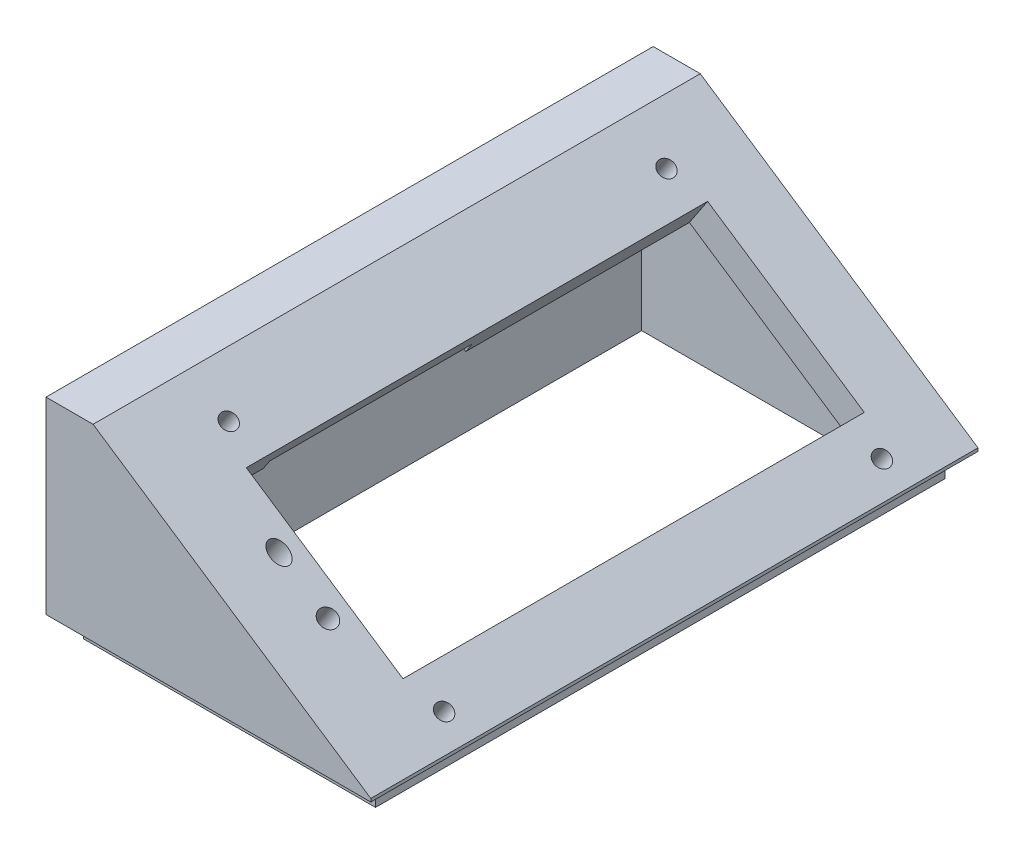
SolidWorks part; units mm, degrees
ref_plane "Front Plane" through (0, 0, 0) normal (0, 0, 1) x (1, 0, 0)
ref_plane "Top Plane" through (0, 0, 0) normal (0, 1, 0) x (1, 0, 0)
ref_plane "Right Plane" through (0, 0, 0) normal (1, 0, 0) x (0, 0, -1)
sketch "Sketch1" plane through (0, 0, 0) normal (0, 0, 1) x (1, 0, 0)
  line L0 (0, 0) -> (70, 0)
  line L1 (0, 0) -> (0, 40)
  line L3 (0, 40) -> (10, 40)
  line L4 (10, 40) -> (70, 0)
  dimension "D1" = 40
  dimension "D2" = 70
  dimension "D3" = 10
extrude "Boss-Extrude1" add sketch "Sketch1" along normal mid plane 129
sketch "Sketch3" plane through (0, 0, 0) normal (0, -1, 0) x (1, 0, 0)
  line L0 (0, 0) -> (4, 0) construction
  line L1 (4, 60.5) -> (66, 60.5)
  line L2 (4, 60.5) -> (4, -60.5)
  line L3 (4, -60.5) -> (66, -60.5)
  line L4 (66, 60.5) -> (66, -60.5)
  line L5 (0, 64.5) -> (0, -64.5) construction
  line L6 (35, 64.5) -> (35, 60.5) construction
  line L7 (0, 64.5) -> (70, 64.5) construction
  line L8 (70, 64.5) -> (70, -64.5) construction
  dimension "D1" = 4
  dimension "D2" = 4
extrude "Boss-Extrude3" add sketch "Sketch3" along normal blind 4.5
ref_plane "Plane1" through (0, 0, 55.5) normal (0, 0, 1) x (1, 0, 0)
sketch "Sketch6" plane through (21.5385, 32.3077, 0) normal (0.5547, 0.8321, 0) x (0.8321, -0.5547, 0)
  line L0 (58.2435, -64.5) -> (-13.8675, -64.5) construction
  line L1 (3.6325, -46.5) -> (43.6325, -46.5)
  line L2 (3.6325, -46.5) -> (3.6325, 51.5)
  line L3 (3.6325, 51.5) -> (43.6325, 51.5)
  line L4 (43.6325, -46.5) -> (43.6325, 51.5)
  line L5 (4.1325, 51) -> (4.1325, -46) construction
  dimension "D1" = 98
  dimension "D2" = 18
  dimension "D3" = 40
  dimension "D4" = 0.5
extrude "Cut-Extrude3" cut sketch "Sketch6" against normal blind 7
sketch "Sketch5" plane through (0, -4.5, 0) normal (0, -1, 0) x (1, 0, 0)
  line L0 (66, 60.5) -> (4, 60.5) construction
  line L1 (6.56, 55.5) -> (63.8, 55.5)
  line L2 (6.56, 55.5) -> (6.56, -55.5)
  line L3 (6.56, -55.5) -> (63.8, -55.5)
  line L4 (63.8, 55.5) -> (63.8, -55.5)
  line L6 (4, 60.5) -> (4, -60.5) construction
  line L8 (4, -60.5) -> (66, -60.5) construction
  line L9 (66, -60.5) -> (66, 60.5) construction
  dimension "D1" = 5
  dimension "D2" = 2.2
  dimension "D3" = 5
  dimension "D4" = 2.56
extrude "Cut-Extrude2" cut sketch "Sketch5" against normal blind 1.23
sketch "Sketch4" plane through (0, 0, 55.5) normal (0, 0, 1) x (1, 0, 0)
  line L3 (63.7805, -4.2666) -> (6.5585, 33.8813)
  line L4 (6.5585, 33.8813) -> (6.5585, -4.5)
  line L6 (53.96, 2.2804) -> (20.678, 24.4684) construction
  line L7 (63.7805, -4.2666) -> (63.7805, -4.5)
  line L8 (63.7805, -4.5) -> (6.5585, -4.5)
  line L9 (95, -4.5) -> (-76.75, -4.5) construction
  dimension "D1" = 1.5
  dimension "D2" = 1.5
extrude "Cut-Extrude1" cut sketch "Sketch4" against normal up to surface (111 mm away) up to face at (35.18, -3.885, -55.5)
sketch "Sketch7" plane through (21.5385, 32.3077, 0) normal (0.5547, 0.8321, 0) x (0.8321, -0.5547, 0)
  line L0 (3.6325, -46.5) -> (43.6325, -46.5) construction
  line L1 (17.3825, -51) -> (29.8825, -51) construction
  line L2 (23.6325, -51) -> (23.6325, -46.5) construction
  line L3 (14.8825, -51) -> (17.3825, -51) construction
  circle A0 centre (29.8825, -51) radius 1.925
  ellipse E0 centre (17.3825, -51) end of major axis (19.8825, -51) minor radius 1.85
  dimension "D1" = 3.85
  dimension "D2" = 12.5
  dimension "D3" = 4.5
extrude "Cut-Extrude4" cut sketch "Sketch7" against normal up to next
hole_wizard "Ø1.0mm Dowel Hole1" positions "Sketch8" profile "Sketch9" hole size "Ø1.0" standard "ANSI Metric"
sketch "Sketch8" plane through (21.5385, 32.3077, 0) normal (0.5547, 0.8321, 0) x (0.8321, -0.5547, 0)
  point P0 (-3.8675, -44)
  point P2 (-3.8675, 49)
  point P4 (51.1325, 49)
  point P6 (51.1325, -44)
sketch "Sketch9" plane through (18.3205, 34.453, 44) normal (0, 0, 1) x (-0.8321, 0.5547, 0)
  line L0 (0, 0) -> (0, 7)
  line L1 (0, 7) -> (1.75, 7)
  line L2 (1.75, 7) -> (1.75, 0)
  line L5 (1.75, 0) -> (0, 0)
  line L11 (0, -6.35) -> (0, 107.95) construction
  dimension "Thru Hole Dia." = 3.5
  dimension "Thru Hole Depth" = 7
sketch "Sketch10" plane through (0, 0, 0) normal (-1, 0, 0) x (0, 0, 1)
  line L0 (64.5, 40) -> (64.5, 0) construction
  line L1 (35.5, 3) -> (55.5, 3)
  line L2 (35.5, 3) -> (35.5, 16)
  line L3 (35.5, 16) -> (55.5, 16)
  line L4 (55.5, 3) -> (55.5, 16)
  line L5 (64.5, 0) -> (-64.5, 0) construction
  dimension "D1" = 20
  dimension "D2" = 13
  dimension "D3" = 9
  dimension "D4" = 3
extrude "Cut-Extrude5" cut sketch "Sketch10" against normal blind 10
sketch "Sketch11" plane through (17.6556, 26.4833, 0) normal (-0.5547, -0.8321, 0) x (0.8321, -0.5547, 0)
  line L0 (3.6325, -51.5) -> (3.6325, 46.5) construction
  line L1 (3.6325, -4) -> (-7.3675, -4)
  line L2 (3.6325, -4) -> (3.6325, 39)
  line L3 (3.6325, 39) -> (-7.3675, 39)
  line L4 (-7.3675, -4) -> (-7.3675, 39)
  line L5 (3.6325, 46.5) -> (43.6325, 46.5) construction
  dimension "D1" = 11
  dimension "D2" = 43
  dimension "D3" = 7.5
extrude "Cut-Extrude6" cut sketch "Sketch11" against normal blind 2.5
sketch "Sketch12" plane through (0, 0, 64.5) normal (0, 0, 1) x (1, 0, 0)
  line L1 (69, -4.0513) -> (71, -4.0513)
  line L2 (69, -4.0513) -> (69, 4.2095)
  line L3 (69, 4.2095) -> (71, 4.2095)
  line L4 (71, -4.0513) -> (71, 4.2095)
  dimension "D1" = 1
  dimension "D2" = 2
extrude "Cut-Extrude7" cut sketch "Sketch12" against normal through all
